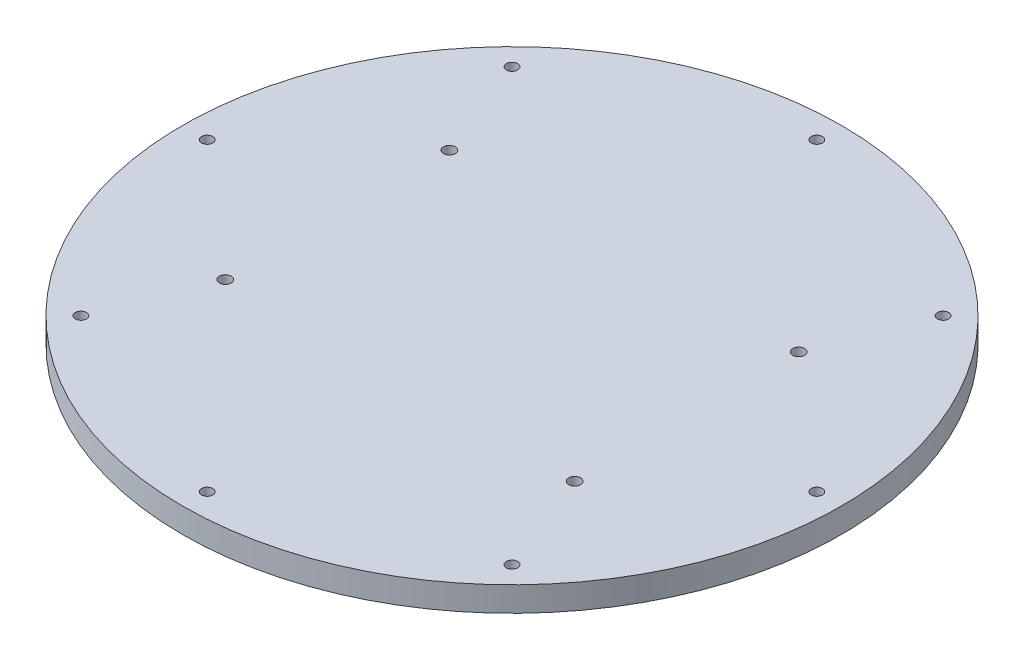
SolidWorks part; units mm, degrees
ref_plane "Front Plane" through (0, 0, 0) normal (0, 0, 1) x (1, 0, 0)
ref_plane "Top Plane" through (0, 0, 0) normal (0, 1, 0) x (1, 0, 0)
ref_plane "Right Plane" through (0, 0, 0) normal (1, 0, 0) x (0, 0, -1)
sketch "Sketch1" plane through (0, 0, 0) normal (0, 1, 0) x (1, 0, 0)
  circle A0 centre (0, 0) radius 100
  dimension "D1" = 200
extrude "Boss-Extrude1" add sketch "Sketch1" along normal blind 7.5
hole_wizard "CBORE for M3 SHCS1" positions "Sketch2" profile "Sketch3" counterbore size "M3" standard "ANSI Metric"
sketch "Sketch2" plane through (0, 0, 0) normal (0, -1, 0) x (-1, 0, 0)
  line L1 (0, -85) -> (0, -100) construction
  line L3 (0, 0) -> (0, -85) construction
  line L4 (0, 0) -> (0, 92.5) construction
  line L6 (0, 0) -> (92.5, 0) construction
  circle A0 centre (0, 0) radius 100 construction
  point P0 (0, -92.5)
  point P17 (-65.4074, -65.4074)
  point P18 (-92.5, 0)
  point P19 (-65.4074, 65.4074)
  point P20 (0, 92.5)
  point P21 (65.4074, 65.4074)
  point P22 (92.5, 0)
  point P23 (65.4074, -65.4074)
  dimension "D1" = 15
  dimension "D2" = 8
sketch "Sketch3" plane through (0, 0, 92.5) normal (1, 0, 0) x (0, 0, -1)
  line L0 (0, 0) -> (0, 8.5215)
  line L1 (0, 8.5215) -> (1.7, 7.5)
  line L2 (1.7, 7.5) -> (1.7, 3)
  line L3 (1.7, 3) -> (3.25, 3)
  line L4 (3.25, 3) -> (3.25, 0)
  line L5 (3.25, 0) -> (0, 0)
  line L10 (0, 8.5215) -> (-1.7, 7.5) construction
  line L11 (0, -6.35) -> (0, 107.95) construction
  dimension "Hole Dia." = 3.4
  dimension "Hole Depth" = 7.5
  dimension "C'Bore Dia." = 6.5
  dimension "C'Bore Depth" = 3
  dimension "Drill Angle" = 118
sketch "Sketch4" plane through (0, 0, 0) normal (0, 1, 0) x (1, 0, 0)
  line L0 (-53, -34) -> (-53, 34) construction
  line L1 (-53, 34) -> (53, 34) construction
  line L2 (53, 34) -> (53, -34) construction
  line L3 (53, -34) -> (-53, -34) construction
  line L4 (0, 34) -> (0, -34) construction
  point P8 (0, 0)
  dimension "D1" = 106
  dimension "D2" = 68
hole_wizard "CBORE for M3 SHCS2" positions "Sketch5" profile "Sketch6" counterbore size "M3" standard "ANSI Metric"
sketch "Sketch5" plane through (0, 0, 0) normal (0, -1, 0) x (-1, 0, 0)
  point P0 (-53, 34)
  point P3 (53, 34)
  point P6 (53, -34)
  point P9 (-53, -34)
sketch "Sketch6" plane through (53, 0, -34) normal (1, 0, 0) x (0, 0, -1)
  line L0 (0, 0) -> (0, 8.5815)
  line L1 (0, 8.5815) -> (1.8, 7.5)
  line L2 (1.8, 7.5) -> (1.8, 3)
  line L3 (1.8, 3) -> (3.25, 3)
  line L4 (3.25, 3) -> (3.25, 0)
  line L5 (3.25, 0) -> (0, 0)
  line L10 (0, 8.5815) -> (-1.8, 7.5) construction
  line L11 (0, -6.35) -> (0, 107.95) construction
  dimension "Hole Dia." = 3.6
  dimension "Hole Depth" = 7.5
  dimension "C'Bore Dia." = 6.5
  dimension "C'Bore Depth" = 3
  dimension "Drill Angle" = 118
sketch "Sketch8" plane through (0, 0, 0) normal (0, 1, 0) x (1, 0, 0)
  line L0 (-45.5873, 116.3907) -> (45.5873, -116.3907)
  point P2 (0, 0)
  dimension "D1" = 250
ref_plane "Plane1" through (0, 0, 0) normal (-0.9311, 0, 0.3647) x (0.3647, 0, 0.9311)
sketch "Sketch9" plane through (0, 0, 0) normal (-0.9311, 0, 0.3647) x (0.3647, 0, 0.9311)
  line L1 (-139.4421, 36.0587) -> (137.3978, 36.0587)
  line L2 (-139.4421, 36.0587) -> (-139.4421, -50.3959)
  line L3 (-139.4421, -50.3959) -> (137.3978, -50.3959)
  line L4 (137.3978, 36.0587) -> (137.3978, -50.3959)
